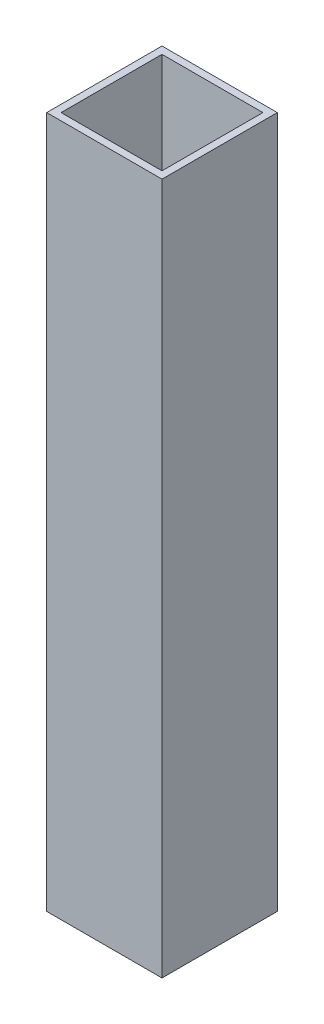
SolidWorks part; units mm, degrees
ref_plane "Front Plane" through (0, 0, 0) normal (0, 0, 1) x (1, 0, 0)
ref_plane "Top Plane" through (0, 0, 0) normal (0, 1, 0) x (1, 0, 0)
ref_plane "Right Plane" through (0, 0, 0) normal (1, 0, 0) x (0, 0, -1)
sketch "Sketch1" plane through (0, 0, 0) normal (0, 1, 0) x (1, 0, 0)
  line L1 (12.7, -12.7) -> (-12.7, -12.7)
  line L2 (12.7, -12.7) -> (12.7, 12.7)
  line L3 (12.7, 12.7) -> (-12.7, 12.7)
  line L4 (-12.7, -12.7) -> (-12.7, 12.7)
  line L5 (12.7, -12.7) -> (-12.7, 12.7) construction
  line L6 (12.7, 12.7) -> (-12.7, -12.7) construction
  line L7 (11.1125, -11.1125) -> (-11.1125, -11.1125)
  line L9 (11.1125, -11.1125) -> (11.1125, 11.1125)
  line L10 (11.1125, 11.1125) -> (-11.1125, 11.1125)
  line L11 (9.9974, -9.9974) -> (-9.9974, 9.9974) construction
  line L12 (9.9974, 9.9974) -> (-9.9974, -9.9974) construction
  line L13 (-11.1125, -11.1125) -> (-11.1125, 11.1125)
  line L14 (11.1125, -11.1125) -> (-11.1125, 11.1125) construction
  line L15 (11.1125, 11.1125) -> (-11.1125, -11.1125) construction
  point P0 (0, 0)
  point P6 (0, 0)
  point P11 (0, 0)
  dimension "D1" = 25.4
  dimension "D2" = 25.4
extrude "Boss-Extrude1" add sketch "Sketch1" along normal blind 152.4
